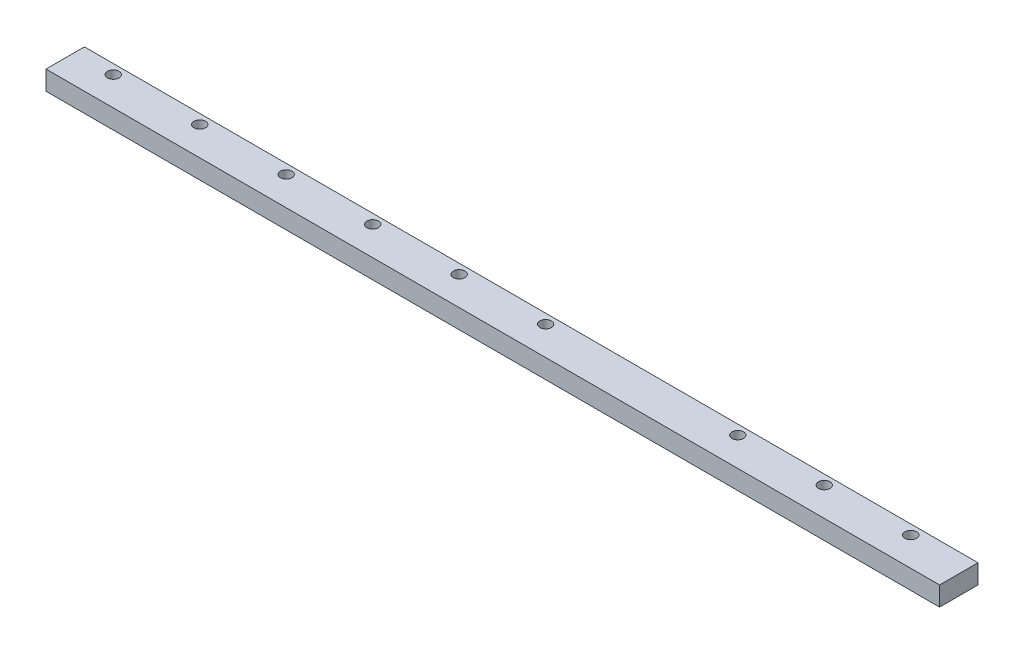
SolidWorks part; units mm, degrees
ref_plane "Front Plane" through (0, 0, 0) normal (0, 0, 1) x (1, 0, 0)
ref_plane "Top Plane" through (0, 0, 0) normal (0, 1, 0) x (1, 0, 0)
ref_plane "Right Plane" through (0, 0, 0) normal (1, 0, 0) x (0, 0, -1)
sketch "Sketch1" plane through (0, 0, 0) normal (0, 1, 0) x (1, 0, 0)
  line L1 (-295.275, -12.7) -> (295.275, -12.7)
  line L2 (-295.275, -12.7) -> (-295.275, 12.7)
  line L3 (-295.275, 12.7) -> (295.275, 12.7)
  line L4 (295.275, -12.7) -> (295.275, 12.7)
  line L5 (-295.275, -12.7) -> (295.275, 12.7) construction
  line L6 (-295.275, 12.7) -> (295.275, -12.7) construction
  point P0 (0, 0)
  dimension "D1" = 590.55
  dimension "D2" = 25.4
extrude "Boss-Extrude1" add sketch "Sketch1" along normal blind 12.7
sketch "Sketch2" plane through (0, 12.7, 0) normal (0, 1, 0) x (1, 0, 0)
  line L0 (295.275, 12.7) -> (-295.275, 12.7) construction
  line L1 (-295.275, 12.7) -> (-295.275, -12.7) construction
  line L2 (-269.875, 6.35) -> (-212.725, 6.35) construction
  line L3 (142.875, 6.35) -> (200.025, 6.35) construction
  point P0 (-269.875, 6.35)
  point P5 (-212.725, 6.35)
  point P6 (142.875, 6.35)
  point P7 (-155.575, 6.35)
  point P8 (-98.425, 6.35)
  point P9 (-41.275, 6.35)
  point P10 (15.875, 6.35)
  point P13 (200.025, 6.35)
  point P14 (257.175, 6.35)
  dimension "D1" = 6.35
  dimension "D2" = 25.4
  dimension "D4" = 57.15
  dimension "D5" = 127
  dimension "D7" = 57.15
  dimension "D3" = 6
  dimension "D6" = 3
hole_wizard "#94 (0.3) Diameter Hole1" positions "Sketch2" profile "Sketch3" hole size "#94" standard "ANSI Inch"
sketch "Sketch3" plane through (-269.875, 12.7, -6.35) normal (1, 0, 0) x (0, 0, 1)
  line L0 (0, 0) -> (0, 14.9893)
  line L1 (0, 14.9893) -> (3.81, 12.7)
  line L2 (3.81, 12.7) -> (3.81, 0)
  line L5 (3.81, 0) -> (0, 0)
  line L10 (0, 14.9893) -> (-3.81, 12.7) construction
  line L11 (0, -6.35) -> (0, 107.95) construction
  dimension "Hole Dia." = 7.62
  dimension "Hole Depth" = 12.7
  dimension "Drill Angle" = 118
